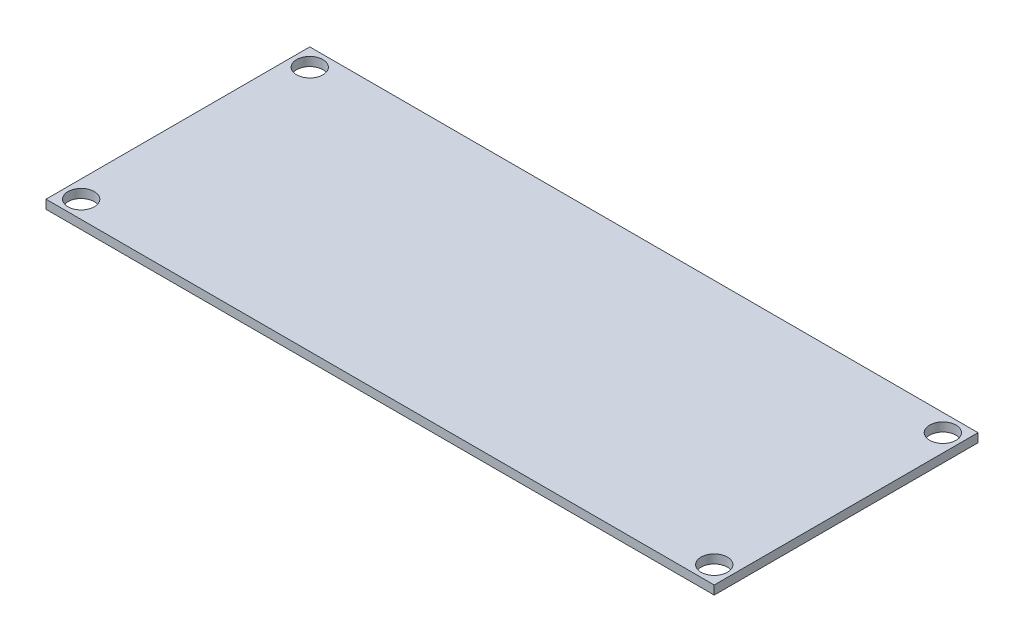
SolidWorks part; units mm, degrees
ref_plane "Alzado" through (0, 0, 0) normal (0, 0, 1) x (1, 0, 0)
ref_plane "Planta" through (0, 0, 0) normal (0, 1, 0) x (1, 0, 0)
ref_plane "Vista lateral" through (0, 0, 0) normal (1, 0, 0) x (0, 0, -1)
sketch "Croquis1" plane through (0, 0, 0) normal (0, 1, 0) x (1, 0, 0)
  line L1 (-38, -15) -> (38, -15)
  line L2 (-38, -15) -> (-38, 15)
  line L3 (-38, 15) -> (38, 15)
  line L4 (38, -15) -> (38, 15)
  line L5 (-38, -15) -> (38, 15) construction
  line L6 (-38, 15) -> (38, -15) construction
  point P0 (0, 0)
  dimension "D1" = 30
  dimension "D2" = 76
extrude "Saliente-Extruir1" add sketch "Croquis1" along normal blind 1
hole_wizard "Taladro de margen para M31" positions "Croquis3D1" profile "Croquis3" hole size "M3" standard "Ansi Metric" end condition up to next
sketch3d "Croquis3D1"
  line L0 (38, 1, 15) -> (38, 1, -15) construction
  line L1 (38, 1, -15) -> (-38, 1, -15) construction
  line L2 (-38, 1, 15) -> (38, 1, 15) construction
  line L3 (-38, 1, -15) -> (-38, 1, 15) construction
  point P0 (-36, 1, -13)
  point P2 (36, 1, -13)
  point P4 (36, 1, 13)
  point P6 (-36, 1, 13)
  dimension "D1" = 2
  dimension "D2" = 2
  dimension "D3" = 2
  dimension "D4" = 2
sketch "Croquis3" plane through (-36, 1, -13) normal (1, 0, 0) x (0, 0, 1)
  line L0 (0, 0) -> (0, 1)
  line L1 (0, 1) -> (1.5, 1)
  line L2 (1.5, 1) -> (1.5, 0)
  line L5 (1.5, 0) -> (0, 0)
  line L11 (0, -6.35) -> (0, 107.95) construction
  dimension "Diámetro de taladro hasta el siguiente" = 3
  dimension "Profundidad de taladro hasta el siguiente" = 1
